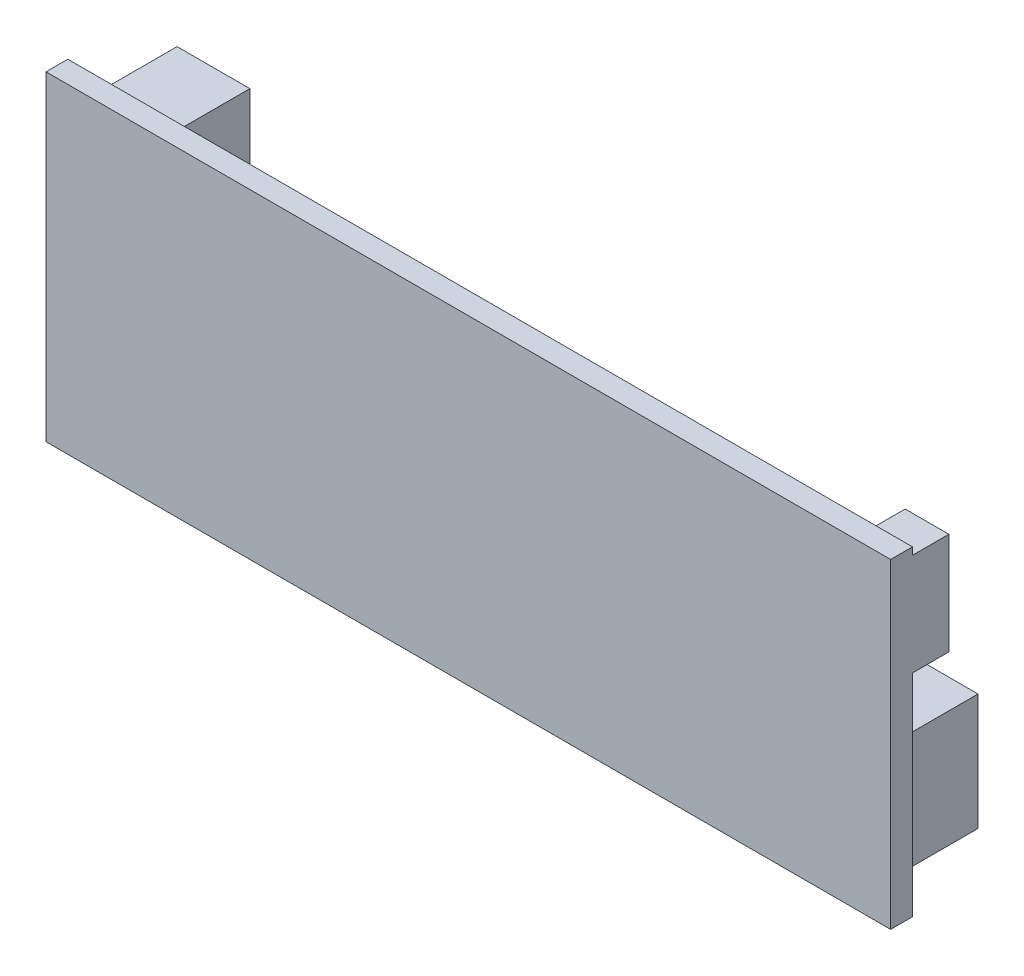
SolidWorks part; units mm, degrees
ref_plane "Front Plane" through (0, 0, 0) normal (0, 0, 1) x (1, 0, 0)
ref_plane "Top Plane" through (0, 0, 0) normal (0, 1, 0) x (1, 0, 0)
ref_plane "Right Plane" through (0, 0, 0) normal (1, 0, 0) x (0, 0, -1)
sketch "Sketch1" plane through (0, 0, 0) normal (0, 0, 1) x (1, 0, 0)
  line L0 (-19.2815, 22) -> (-19.2815, 0)
  line L4 (-19.2815, 22) -> (38.7185, 22)
  line L5 (38.7185, 22) -> (38.7185, 0)
  line L6 (38.7185, 0) -> (-19.2815, 0)
extrude "Boss-Extrude1" add sketch "Sketch1" along normal blind 1.5
sketch "Sketch2" plane through (0, 0, 0) normal (0, 0, -1) x (-1, 0, 0)
  line L1 (17.7815, 20.5) -> (12.7815, 20.5)
  line L2 (17.7815, 20.5) -> (17.7815, 15.5)
  line L3 (17.7815, 15.5) -> (12.7815, 15.5)
  line L4 (12.7815, 20.5) -> (12.7815, 15.5)
  line L15 (19.2815, 22) -> (19.2815, 0) construction
  line L16 (17.7815, 7.9) -> (19.2815, 7.9)
  line L17 (17.7815, 7.9) -> (17.7815, 3.0979)
  line L18 (17.7815, 3.0979) -> (19.2815, 3.0979)
  line L19 (19.2815, 7.9) -> (19.2815, 3.0979)
  line L20 (32.1478, 3.0979) -> (17.1478, 3.0979) construction
  line L22 (-38.7185, 0) -> (-38.7185, 22) construction
  line L23 (-38.7185, 21.5) -> (-35.7185, 21.5)
  line L24 (-38.7185, 21.5) -> (-38.7185, 14.5)
  line L25 (-38.7185, 14.5) -> (-35.7185, 14.5)
  line L26 (-35.7185, 21.5) -> (-35.7185, 14.5)
  line L27 (19.2815, 0) -> (-38.7185, 0) construction
  line L32 (-37.2185, 1.5) -> (-29.2185, 1.5)
  line L33 (-37.2185, 1.5) -> (-37.2185, 9.5)
  line L34 (-37.2185, 9.5) -> (-29.2185, 9.5)
  line L35 (-29.2185, 1.5) -> (-29.2185, 9.5)
  dimension "D1" = 5
  dimension "D2" = 5
  dimension "D3" = 3
  dimension "D4" = 1.5
  dimension "D5" = 1.5
  dimension "D6" = 8
extrude "Boss-Extrude2" add sketch "Sketch2" along normal blind 2.5
sketch "Sketch3" plane through (0, 0, -2.5) normal (0, 0, -1) x (-1, 0, 0)
  line L0 (17.7815, 7.9) -> (17.7815, 3.0979) construction
  line L1 (17.7815, 3.0979) -> (19.2815, 3.0979) construction
  line L2 (19.2815, 3.0979) -> (19.2815, 7.9) construction
  line L3 (19.2815, 7.9) -> (17.7815, 7.9) construction
  line L4 (17.7815, 15.5) -> (17.7815, 20.5) construction
  line L5 (17.7815, 20.5) -> (12.7815, 20.5) construction
  line L6 (12.7815, 20.5) -> (12.7815, 15.5) construction
  line L7 (12.7815, 15.5) -> (17.7815, 15.5) construction
  line L8 (-37.2185, 9.5) -> (-37.2185, 1.5) construction
  line L9 (-37.2185, 1.5) -> (-29.2185, 1.5) construction
  line L10 (-29.2185, 1.5) -> (-29.2185, 9.5) construction
  line L11 (-29.2185, 9.5) -> (-37.2185, 9.5) construction
  line L12 (17.7815, 7.9) -> (17.7815, 3.0979)
  line L13 (17.7815, 3.0979) -> (19.2815, 3.0979)
  line L14 (19.2815, 3.0979) -> (19.2815, 7.9)
  line L15 (19.2815, 7.9) -> (17.7815, 7.9)
  line L16 (17.7815, 15.5) -> (17.7815, 20.5)
  line L17 (17.7815, 20.5) -> (12.7815, 20.5)
  line L18 (12.7815, 20.5) -> (12.7815, 15.5)
  line L19 (12.7815, 15.5) -> (17.7815, 15.5)
  line L20 (-37.2185, 9.5) -> (-37.2185, 1.5)
  line L21 (-37.2185, 1.5) -> (-29.2185, 1.5)
  line L22 (-29.2185, 1.5) -> (-29.2185, 9.5)
  line L23 (-29.2185, 9.5) -> (-37.2185, 9.5)
extrude "Boss-Extrude3" add sketch "Sketch3" along normal blind 3.5
